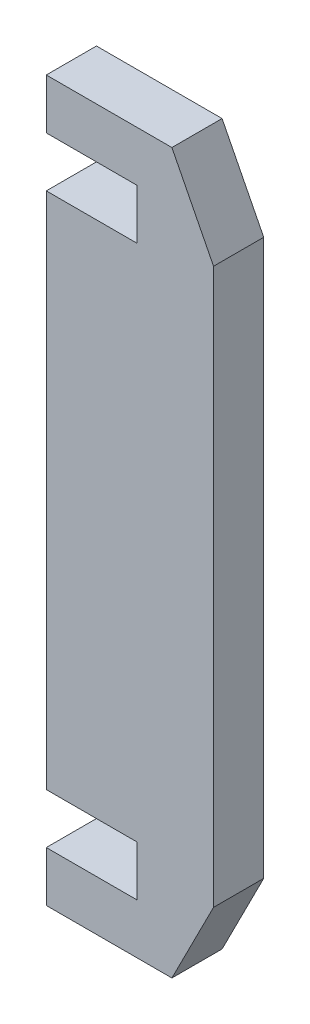
SolidWorks part; units mm, degrees
ref_plane "Front" through (0, 0, 0) normal (0, 0, 1) x (1, 0, 0)
ref_plane "Top" through (0, 0, 0) normal (0, 1, 0) x (1, 0, 0)
ref_plane "Right" through (0, 0, 0) normal (1, 0, 0) x (0, 0, -1)
sketch "Sketch1" plane through (0, 0, 0) normal (0, 0, 1) x (1, 0, 0)
  line L0 (882.9097, -114.5171) -> (882.9097, -81.3234)
  line L1 (878.3186, -79.4203) -> (878.3186, -82.4203)
  line L2 (878.3186, -113.4203) -> (878.3186, -116.4203)
  line L3 (880.4198, -119.4203) -> (882.9097, -114.5171)
  line L4 (872.9097, -119.4203) -> (872.9097, -116.4203)
  line L5 (872.9097, -119.4203) -> (880.4198, -119.4203)
  line L6 (872.9097, -82.4203) -> (872.9097, -103.4996)
  line L7 (878.3186, -116.4203) -> (872.9097, -116.4203)
  line L9 (878.3186, -79.4203) -> (872.9097, -79.4203)
  line L10 (872.9097, -76.4203) -> (880.4198, -76.4203)
  line L11 (872.9097, -79.4203) -> (872.9097, -76.4203)
  line L12 (880.4198, -76.4203) -> (882.9097, -81.3234)
  line L14 (872.9097, -82.4203) -> (878.3186, -82.4203)
  line L15 (872.9097, -113.4203) -> (872.9097, -103.4996)
  line L16 (872.9097, -113.4203) -> (878.3186, -113.4203)
  dimension "D1" = 3
  dimension "D2" = 3
  dimension "D3" = 3
  dimension "D4" = 43
  dimension "D5" = 3
  dimension "D6" = 10
extrude "Base-Extrude" add sketch "Sketch1" along normal blind 3
